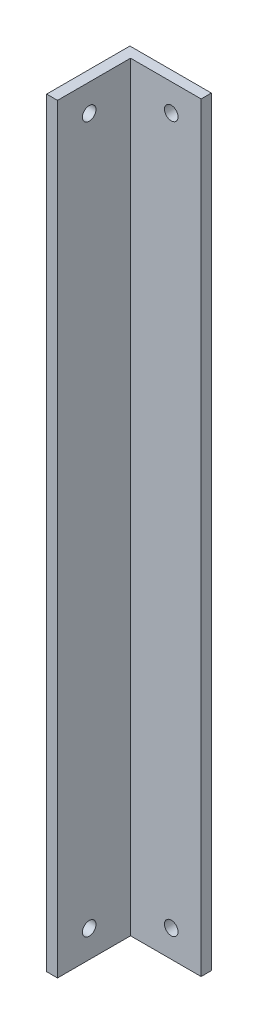
SolidWorks part; units mm, degrees
ref_plane "前视基准面" through (0, 0, 0) normal (0, 0, 1) x (1, 0, 0)
ref_plane "上视基准面" through (0, 0, 0) normal (0, 1, 0) x (1, 0, 0)
ref_plane "右视基准面" through (0, 0, 0) normal (1, 0, 0) x (0, 0, -1)
other "图形1"
sketch "草图1" plane through (0, 0, 0) normal (0, 1, 0) x (1, 0, 0)
  line L0 (-119.2398, 232.2401) -> (-89.2398, 232.2401)
  line L3 (-115.2398, 228.4708) -> (-89.2398, 228.4708)
  line L4 (-89.2398, 232.2401) -> (-89.2398, 228.4708)
  line L5 (-119.2398, 232.2401) -> (-119.2398, 228.2312)
  line L7 (-119.2398, 228.2312) -> (-119.2398, 201.5611)
  line L8 (-119.2398, 201.5611) -> (-115.2398, 201.5611)
  line L9 (-115.2398, 201.5611) -> (-115.2398, 228.4708)
  dimension "D1" = 30
extrude "凸台-拉伸1" add sketch "草图1" along normal blind 280
hole_wizard "M6 螺纹孔3" positions "草图9" profile "草图8" tap size "M6" standard "GB"
sketch "草图9" plane through (-119.2398, 0, 0) normal (-1, 0, 0) x (0, 0, 1)
  line L0 (-232.2401, 280) -> (-232.2401, 0) construction
  point P9 (-213.2401, 10)
  point P10 (-213.2401, 270)
  point P14 (0, 0)
  point P15 (0, 0)
  point P16 (0, 0)
  point P17 (0, 0)
  dimension "D1" = 19
  dimension "D2" = 10
  dimension "D3" = 260
sketch "草图8" plane through (-119.2398, 10, -213.2401) normal (0, 1, 0) x (0, 0, 1)
  line L0 (0, 0) -> (0, 18.5022)
  line L1 (0, 18.5022) -> (2.5, 17)
  line L2 (2.5, 17) -> (2.5, 0)
  line L5 (2.5, 0) -> (0, 0)
  line L10 (0, 18.5022) -> (-2.5, 17) construction
  line L11 (0, -6.35) -> (0, 107.95) construction
  dimension "螺纹孔钻头直径" = 5
  dimension "螺纹孔钻头深度" = 17
  dimension "导头角度" = 118
hole_wizard "M6 螺纹孔4" positions "草图11" profile "草图10" tap size "M6" standard "GB"
sketch "草图11" plane through (0, 0, -232.2401) normal (0, 0, -1) x (-1, 0, 0)
  line L0 (119.2398, 280) -> (119.2398, 0) construction
  point P9 (100.2398, 10)
  point P10 (100.2398, 270)
  point P14 (0, 0)
  point P15 (0, 0)
  dimension "D1" = 19
  dimension "D2" = 10
  dimension "D3" = 260
sketch "草图10" plane through (-100.2398, 10, -232.2401) normal (1, 0, 0) x (0, 1, 0)
  line L0 (0, 0) -> (0, 18.5022)
  line L1 (0, 18.5022) -> (2.5, 17)
  line L2 (2.5, 17) -> (2.5, 0)
  line L5 (2.5, 0) -> (0, 0)
  line L10 (0, 18.5022) -> (-2.5, 17) construction
  line L11 (0, -6.35) -> (0, 107.95) construction
  dimension "螺纹孔钻头直径" = 5
  dimension "螺纹孔钻头深度" = 17
  dimension "导头角度" = 118
